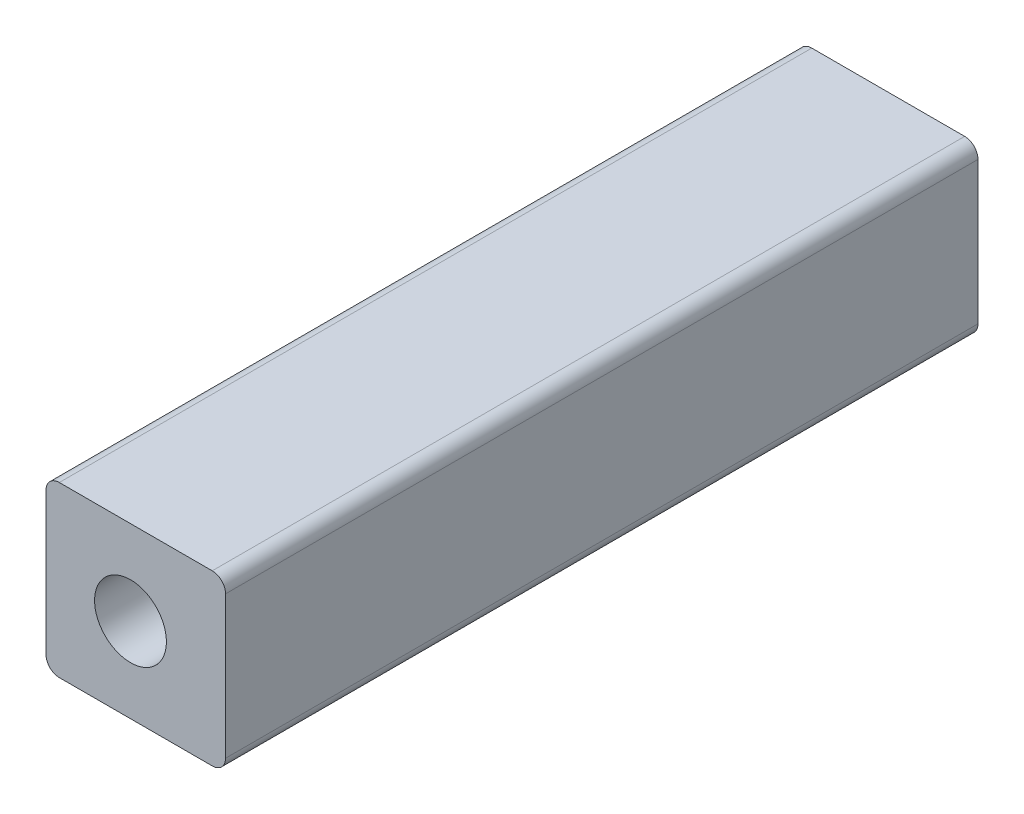
SolidWorks part; units mm, degrees
material "ABS"
ref_plane "X-Y Datum" through (0, 0, 0) normal (0, 0, 1) x (1, 0, 0)
ref_plane "X-Z Datum" through (0, 0, 0) normal (0, 1, 0) x (1, 0, 0)
ref_plane "Y-Z Datum" through (0, 0, 0) normal (1, 0, 0) x (0, 0, -1)
sketch "Sketch1" plane through (0, 0, 0) normal (0, 0, 1) x (1, 0, 0)
  line L1 (-6.35, 6.35) -> (6.35, 6.35)
  line L2 (-6.35, 6.35) -> (-6.35, -6.35)
  line L3 (-6.35, -6.35) -> (6.35, -6.35)
  line L4 (6.35, 6.35) -> (6.35, -6.35)
  line L5 (-6.35, 6.35) -> (6.35, -6.35) construction
  line L6 (-6.35, -6.35) -> (6.35, 6.35) construction
  circle A0 centre (0, 0) radius 2.7
  point P0 (0, 0)
  dimension "D1" = 5.4
  dimension "D2" = 12.7
  dimension "D3" = 12.7
extrude "Boss-Extrude1" add sketch "Sketch1" along normal mid plane 56.55
sketch "Sketch4" plane through (6.35, 0, 0) normal (1, 0, 0) x (0, 0, -1)
  line L4 (28.275, -6.35) -> (28.275, 6.35)
  line L5 (28.275, 6.35) -> (-28.275, 6.35)
  line L6 (-28.275, 6.35) -> (-28.275, -6.35)
  line L7 (-28.275, -6.35) -> (28.275, -6.35)
  line L8 (28.275, -6.35) -> (28.275, 6.35)
  line L9 (28.275, 6.35) -> (-28.275, 6.35)
  line L10 (-28.275, 6.35) -> (-28.275, -6.35)
  line L11 (-28.275, -6.35) -> (28.275, -6.35)
  dimension "D1" = 0
extrude "Boss-Extrude3" add sketch "Sketch4" along normal blind 0.7937
fillet "Fillet2" radius 1 4 edges at (-6.35, -6.35, 0) (-6.35, 6.35, 0) (7.1437, 6.35, 0) (7.1438, -6.35, 0)
